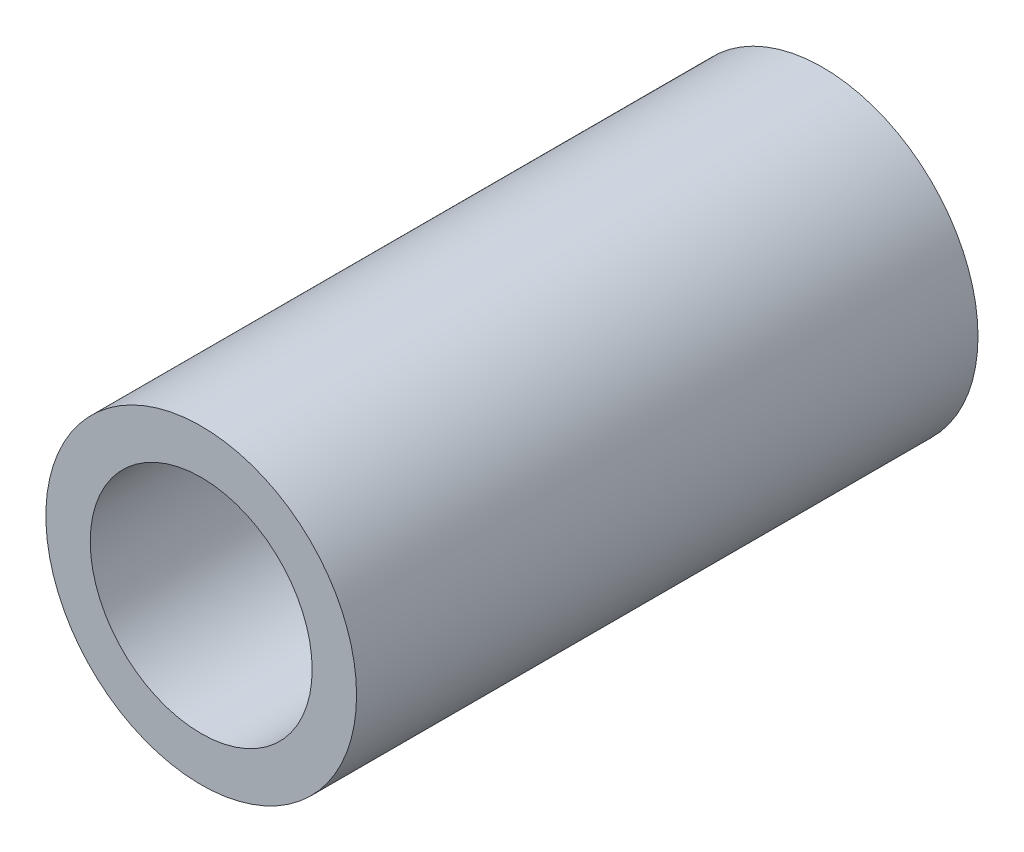
SolidWorks part; units mm, degrees
ref_plane "Front Plane" through (0, 0, 0) normal (0, 0, 1) x (1, 0, 0)
ref_plane "Top Plane" through (0, 0, 0) normal (0, 1, 0) x (1, 0, 0)
ref_plane "Right Plane" through (0, 0, 0) normal (1, 0, 0) x (0, 0, -1)
sketch "Sketch1" plane through (0, 0, 0) normal (0, 0, 1) x (1, 0, 0)
  circle A0 centre (0, 0) radius 3.5
  circle A1 centre (0, 0) radius 2.5
  dimension "D1" = 5
  dimension "D2" = 7
extrude "Boss-Extrude1" add sketch "Sketch1" along normal blind 14
